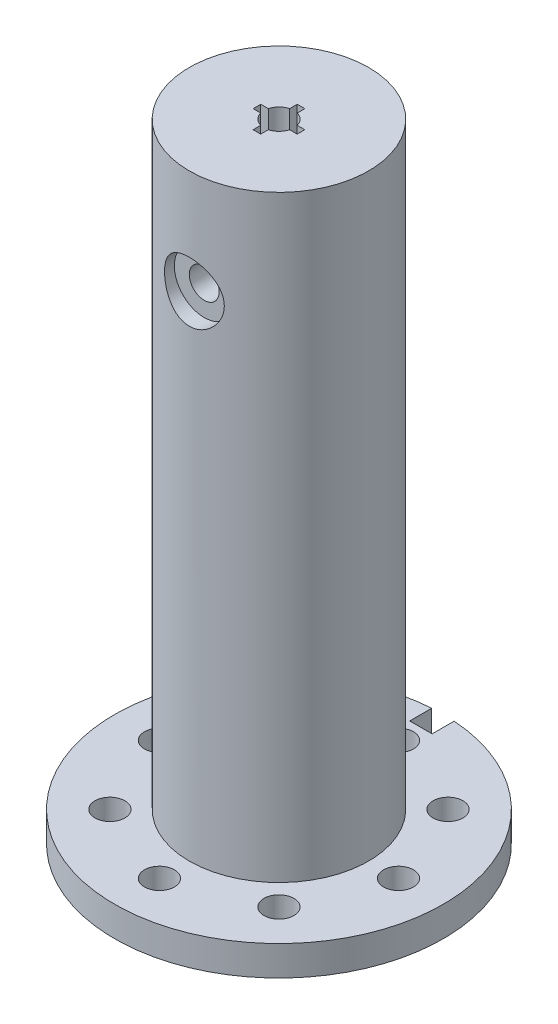
SolidWorks part; units mm, degrees
material "1060 Alloy"
ref_plane "Front Plane" through (0, 0, 0) normal (0, 0, 1) x (1, 0, 0)
ref_plane "Top Plane" through (0, 0, 0) normal (0, 1, 0) x (1, 0, 0)
ref_plane "Right Plane" through (0, 0, 0) normal (1, 0, 0) x (0, 0, -1)
sketch "Sketch1" plane through (0, 0, 0) normal (0, 1, 0) x (1, 0, 0)
  circle A0 centre (0, 0) radius 11
  circle A1 centre (0, 8) radius 1
  circle A2 centre (5.6569, 5.6569) radius 1
  circle A3 centre (8, 0) radius 1
  circle A4 centre (5.6569, -5.6569) radius 1
  circle A5 centre (0, -8) radius 1
  circle A6 centre (-5.6569, -5.6569) radius 1
  circle A7 centre (-8, 0) radius 1
  circle A8 centre (-5.6569, 5.6569) radius 1
  point P22 (0, 0)
  dimension "D1" = 22
  dimension "D2" = 2
  dimension "D6" = 8
  dimension "D3" = 8
  dimension "D5" = 8
  dimension "D4" = 8
extrude "Boss-Extrude1" add sketch "Sketch1" along normal blind 2
sketch "Sketch2" plane through (0, 2, 0) normal (0, 1, 0) x (1, 0, 0)
  circle A0 centre (0, 0) radius 4
  dimension "D1" = 8
extrude "Cut-Extrude1" cut sketch "Sketch2" against normal through all
ref_plane "Plane1" through (0, 0, 0) normal (0, 1, 0) x (1, 0, 0)
sketch "Sketch3" plane through (0, 0, 0) normal (0, 1, 0) x (1, 0, 0)
  circle A0 centre (0, 0) radius 5
  circle A1 centre (0, 0) radius 11
  dimension "D1" = 10
  dimension "D2" = 22
sketch "Sketch4" plane through (0, 2, 0) normal (0, 1, 0) x (1, 0, 0)
  line L1 (-0.75, 12.5) -> (0.75, 12.5)
  line L2 (-0.75, 12.5) -> (-0.75, 9.5)
  line L3 (-0.75, 9.5) -> (0.75, 9.5)
  line L4 (0.75, 12.5) -> (0.75, 9.5)
  line L5 (-0.75, 12.5) -> (0.75, 9.5) construction
  line L6 (-0.75, 9.5) -> (0.75, 12.5) construction
  circle A0 centre (0, 0) radius 11 construction
  point P0 (0, 11)
  dimension "D1" = 1.5
  dimension "D2" = 3
extrude "Cut-Extrude3" cut sketch "Sketch4" against normal blind 4
sketch "Sketch5" plane through (0, 2, 0) normal (0, 1, 0) x (1, 0, 0)
  circle A0 centre (0, 0) radius 4
  circle A1 centre (0, 0) radius 6
  dimension "D1" = 8
  dimension "D2" = 12
extrude "Boss-Extrude2" add sketch "Sketch5" along normal blind 20 contours A1 | A0
sketch "Sketch6" plane through (0, 22, 0) normal (0, 1, 0) x (1, 0, 0)
  line L0 (-0.255, 0.9669) -> (0.255, 0.9669)
  line L1 (-0.255, 0.9669) -> (-0.255, 1.4769)
  line L2 (0.255, 0.9669) -> (0.255, 1.4769)
  line L3 (-0.255, 1.4769) -> (0.255, 1.4769)
  line L4 (-0.254, -0.9672) -> (0.254, -0.9672)
  line L5 (-0.254, -0.9672) -> (-0.254, -1.4752)
  line L6 (0.254, -0.9672) -> (0.254, -1.4752)
  line L7 (-0.254, -1.4752) -> (0.254, -1.4752)
  line L8 (0.9672, 0.254) -> (0.9672, -0.254)
  line L9 (0.9672, 0.254) -> (1.4752, 0.254)
  line L10 (0.9672, -0.254) -> (1.4752, -0.254)
  line L11 (1.4752, 0.254) -> (1.4752, -0.254)
  line L12 (-0.9672, 0.254) -> (-0.9672, -0.254)
  line L13 (-0.9672, 0.254) -> (-1.4752, 0.254)
  line L14 (-0.9672, -0.254) -> (-1.4752, -0.254)
  line L15 (-1.4752, 0.254) -> (-1.4752, -0.254)
  circle A0 centre (0, 0) radius 1
  circle A1 centre (0, 0) radius 4
  circle A2 centre (0, 0) radius 6
  circle M4 centre (0, 0) radius 6
  circle M5 centre (0, 0) radius 4
  dimension "D1" = 2
  dimension "D4" = 8
  dimension "D5" = 12
  dimension "D2" = 0.51
  dimension "D3" = 0.51
  dimension "D6" = 0.508
  dimension "D7" = 0.508
  dimension "D8" = 0.508
  dimension "D9" = 0.508
  dimension "D10" = 0.508
  dimension "D11" = 0.508
extrude "Boss-Extrude3" add sketch "Sketch6" along normal blind 20 contours A0 L1 L3 L2 M5 | M4 M5
sketch "Sketch7" plane through (0, 0, 0) normal (0, 0, 1) x (1, 0, 0)
  line L0 (11, 0) -> (-11, 0) construction
  circle A0 centre (0, 35) radius 1
  dimension "D1" = 2
  dimension "D2" = 35
extrude "Cut-Extrude4" cut sketch "Sketch7" against normal blind 1 and the other way blind 5
ref_plane "Plane2" through (0, 0, 6) normal (0, 0, 1) x (1, 0, 0)
sketch "Sketch8" plane through (0, 0, 6) normal (0, 0, 1) x (1, 0, 0)
  circle A0 centre (0, 35) radius 2
  dimension "D1" = 4
extrude "Cut-Extrude5" cut sketch "Sketch8" against normal blind 1
